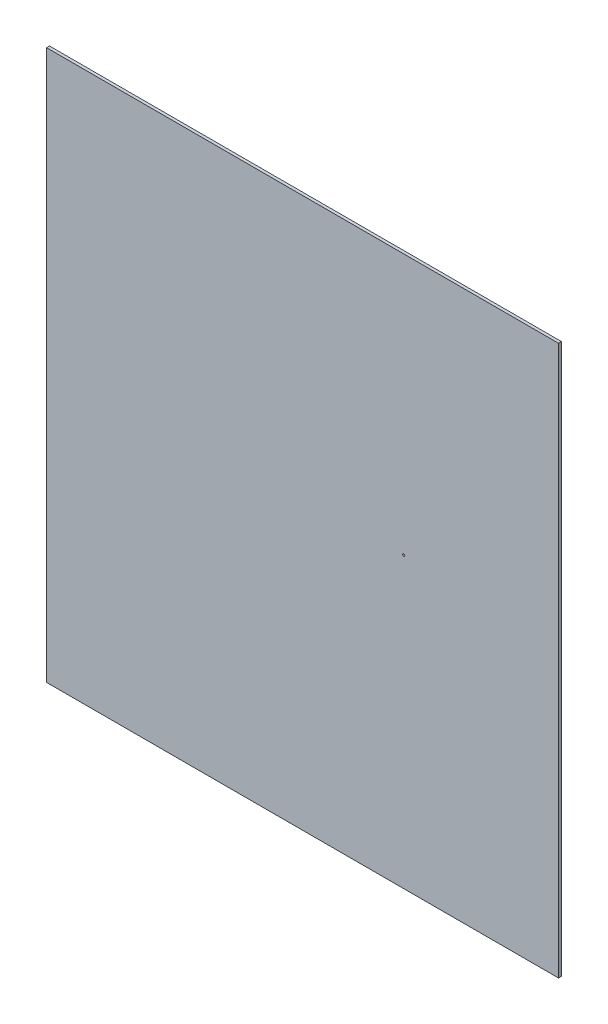
SolidWorks part; units mm, degrees
ref_plane "Спереди" through (0, 0, 0) normal (0, 0, 1) x (1, 0, 0)
ref_plane "Сверху" through (0, 0, 0) normal (0, 1, 0) x (1, 0, 0)
ref_plane "Справа" through (0, 0, 0) normal (1, 0, 0) x (0, 0, -1)
sketch "Эскиз1" plane through (0, 0, 0) normal (0, 0, 1) x (1, 0, 0)
  line L0 (94.897, 22.1621) -> (-25.2024, 22.1621) construction
  line L5 (25.4, 22.6621) -> (94.397, 22.6621)
  line L6 (94.397, 22.6621) -> (94.397, 96.7616)
  line L7 (94.397, 96.7616) -> (25.4, 96.7616)
  line L8 (25.4, 96.7616) -> (25.4, 22.6621)
  line L9 (-20.2024, 97.2616) -> (99.897, 97.2616) construction
  line L11 (94.897, 97.2616) -> (94.897, 17.1621) construction
  dimension "D1" = 0.5
  dimension "D2" = 0.5
  dimension "D3" = 0.5
extrude "Board" add sketch "Эскиз1" along normal blind 0.3912
sketch "Эскиз2" plane through (0, 0, 0.3912) normal (0, 0, 1) x (1, 0, 0)
  circle A0 centre (73.533, 61.595) radius 0.15
extrude "Вырез-Вытянуть1" cut sketch "Эскиз2" against normal blind 0.3912
